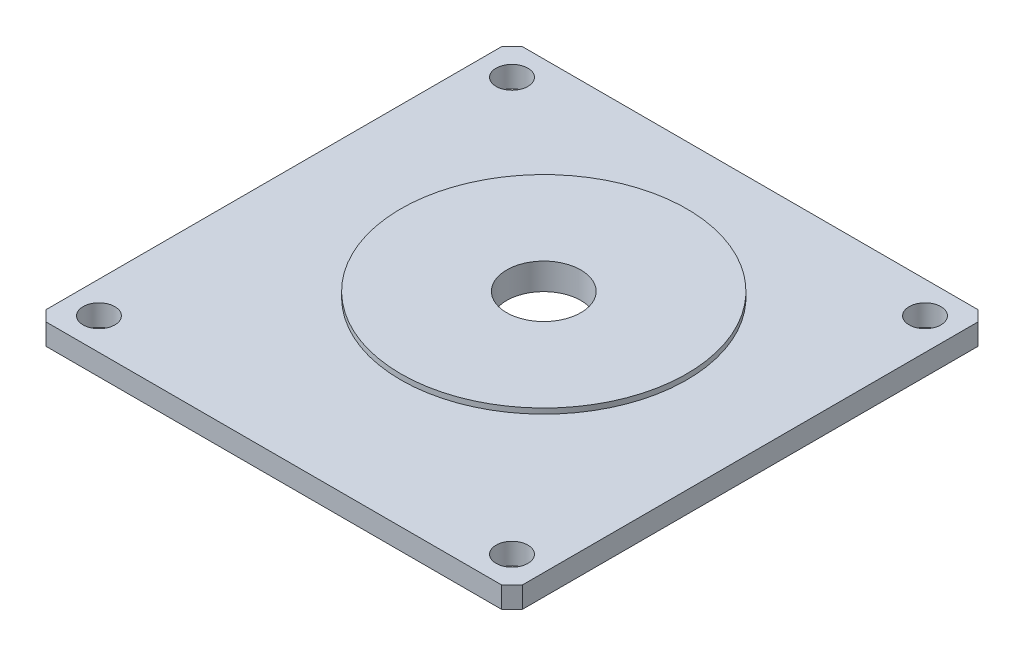
SolidWorks part; units mm, degrees
ref_plane "前视基准面" through (0, 0, 0) normal (0, 0, 1) x (1, 0, 0)
ref_plane "上视基准面" through (0, 0, 0) normal (0, 1, 0) x (1, 0, 0)
ref_plane "右视基准面" through (0, 0, 0) normal (1, 0, 0) x (0, 0, -1)
sketch "草图1" plane through (0, 0, 0) normal (0, 1, 0) x (1, 0, 0)
  line L1 (-22.5, -22.5) -> (22.5, -22.5)
  line L2 (-22.5, -22.5) -> (-22.5, 22.5)
  line L3 (-22.5, 22.5) -> (22.5, 22.5)
  line L4 (22.5, -22.5) -> (22.5, 22.5)
  line L5 (-22.5, -22.5) -> (22.5, 22.5) construction
  line L6 (-22.5, 22.5) -> (22.5, -22.5) construction
  point P0 (0, 0)
  dimension "D1" = 45
  dimension "D2" = 45
extrude "凸台-拉伸1" add sketch "草图1" along normal blind 2
sketch "草图2" plane through (0, 2, 0) normal (0, 1, 0) x (1, 0, 0)
  line L0 (0, 0) -> (0, 3) construction
  circle A0 centre (0, 3) radius 3.5
  dimension "D2" = 7
  dimension "D1" = 3
extrude "切除-拉伸1" cut sketch "草图2" against normal through all
sketch "草图3" plane through (0, 2, 0) normal (0, 1, 0) x (1, 0, 0)
  circle A0 centre (0, 3) radius 13.5
  circle A1 centre (0, 3) radius 3.5 construction
  circle A2 centre (0, 3) radius 3.5
  dimension "D1" = 27
extrude "凸台-拉伸2" add sketch "草图3" along normal blind 0.5
sketch "草图4" plane through (0, 0, 0) normal (0, 1, 0) x (1, 0, 0)
  line L0 (0, 22.5) -> (0, -22.5) construction
  line L1 (22.5, 22.5) -> (-22.5, 22.5) construction
  line L2 (-22.5, -22.5) -> (22.5, -22.5) construction
  line L3 (22.5, 0) -> (-22.5, 0) construction
  line L4 (22.5, -22.5) -> (22.5, 22.5) construction
  line L5 (-22.5, 22.5) -> (-22.5, -22.5) construction
  line L6 (22.5, 22.5) -> (-22.5, 22.5) construction
  circle A0 centre (19.5, 19.5) radius 1.5
  circle A1 centre (-19.5, 19.5) radius 1.5
  circle A2 centre (-19.5, -19.5) radius 1.5
  circle A3 centre (19.5, -19.5) radius 1.5
  dimension "D1" = 3
  dimension "D2" = 3
  dimension "D3" = 3
extrude "切除-拉伸4" cut sketch "草图4" along normal through all
chamfer "倒角1" distance 1 angle 45 4 edges at (-22.5, 1, 22.5) (22.5, 1, 22.5) (-22.5, 1, -22.5) (22.5, 1, -22.5)
